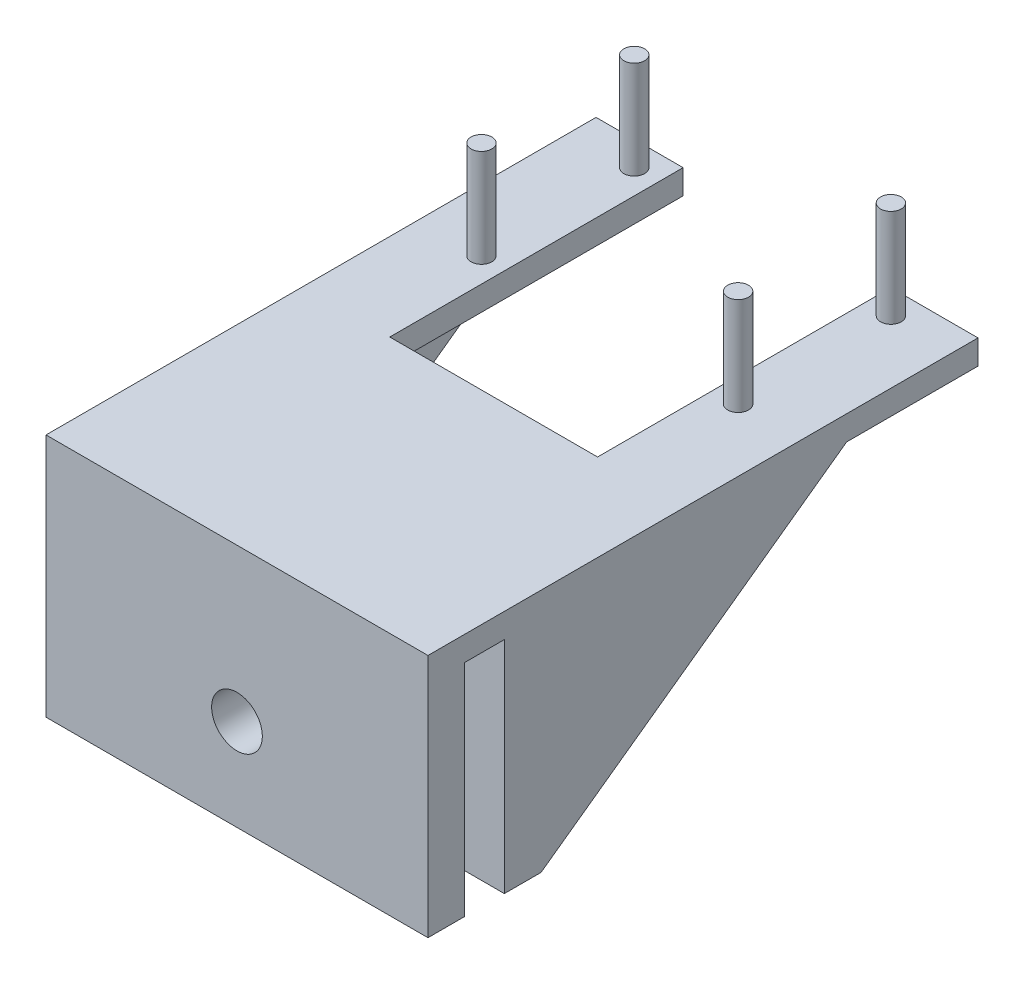
SolidWorks part; units mm, degrees
ref_plane "Front Plane" through (0, 0, 0) normal (0, 0, 1) x (1, 0, 0)
ref_plane "Top Plane" through (0, 0, 0) normal (0, 1, 0) x (1, 0, 0)
ref_plane "Right Plane" through (0, 0, 0) normal (1, 0, 0) x (0, 0, -1)
sketch "Sketch2" plane through (0, 0, 0) normal (0, 1, 0) x (1, 0, 0)
  line L0 (0, 0) -> (0, 45)
  line L1 (0, 45) -> (7.125, 45)
  line L2 (7.125, 45) -> (7.125, 21)
  line L3 (7.125, 21) -> (24.125, 21)
  line L4 (24.125, 21) -> (24.125, 45)
  line L5 (24.125, 45) -> (31.25, 45)
  line L6 (31.25, 45) -> (31.25, 0)
  line L7 (31.25, 0) -> (0, 0)
  point P8 (15.625, 0)
  point P10 (15.625, 21)
  dimension "D1" = 31.25
  dimension "D2" = 17
  dimension "D4" = 45
  dimension "D5" = 24
  dimension "D6" = 24
extrude "Boss-Extrude1" add sketch "Sketch2" along normal blind 2
sketch "Sketch3" plane through (0, 2, 0) normal (0, 1, 0) x (1, 0, 0)
  line L0 (31.25, 45) -> (24.125, 45) construction
  line L1 (7.125, 45) -> (0, 45) construction
  line L3 (7.125, 21) -> (7.125, 45) construction
  circle A0 centre (5.125, 43) radius 0.85
  circle A1 centre (5.125, 30.5) radius 0.85
  circle A2 centre (26.125, 30.5) radius 0.85
  circle A3 centre (26.125, 43) radius 0.85
  dimension "D4" = 1.7
  dimension "D5" = 1.7
  dimension "D6" = 1.7
  dimension "D7" = 1.7
  dimension "D1" = 2
  dimension "D2" = 2
  dimension "D3" = 21
  dimension "D8" = 12.5
  dimension "D9" = 12.5
  dimension "D10" = 2
extrude "Boss-Extrude2" add sketch "Sketch3" along normal blind 8
sketch "Sketch4" plane through (0, 0, 0) normal (0, -1, 0) x (1, 0, 0)
  line L0 (0, 0) -> (31.25, 0)
  line L1 (31.25, 0) -> (31.25, -3)
  line L2 (31.25, 0) -> (31.25, -45) construction
  line L3 (31.25, -3) -> (0, -3)
  line L4 (0, -45) -> (0, 0) construction
  line L5 (0, -3) -> (0, 0)
  line L6 (0, -6.25) -> (31.25, -6.25)
  line L7 (31.25, -6.25) -> (31.25, -9.25)
  line L8 (31.25, -9.25) -> (0, -9.25)
  line L9 (0, -9.25) -> (0, -6.25)
  dimension "D1" = 3
  dimension "D2" = 3.25
  dimension "D3" = 3
extrude "Boss-Extrude3" add sketch "Sketch4" along normal blind 18
sketch "Sketch12" plane through (0, 0, 0) normal (0, 0, 1) x (1, 0, 0)
  line L2 (31.25, 2) -> (31.25, -18) construction
  circle A0 centre (15.625, -10.5) radius 2.075
  dimension "D1" = 4.15
  dimension "D2" = 10.5
  dimension "D3" = 15.625
extrude "Cut-Extrude2" cut sketch "Sketch12" against normal through all
sketch "Sketch13" plane through (0, 0, 0) normal (1, 0, 0) x (0, 0, -1)
  line L0 (34.25, 0) -> (9.25, -18)
  dimension "D1" = 25
  dimension "D2" = 30.8058
rib "Rib1" sketch "Sketch13" sketch "Sketch13" thickness 4 parameters "D1"=4
ref_plane "Plane1" through (31.25, 0, 0) normal (1, 0, 0) x (0, 0, -1)
sketch "Sketch14" plane through (31.25, 0, 0) normal (1, 0, 0) x (0, 0, -1)
  line L0 (34.25, 0) -> (9.25, -18)
  line L1 (9.25, -18) -> (9.25, 0) construction
  dimension "D1" = 25
  dimension "D2" = 30.8058
rib "Rib2" sketch "Sketch14" sketch "Sketch14" thickness 4 extrusion direction parallel to sketch draft on no parameters "D1"=4
